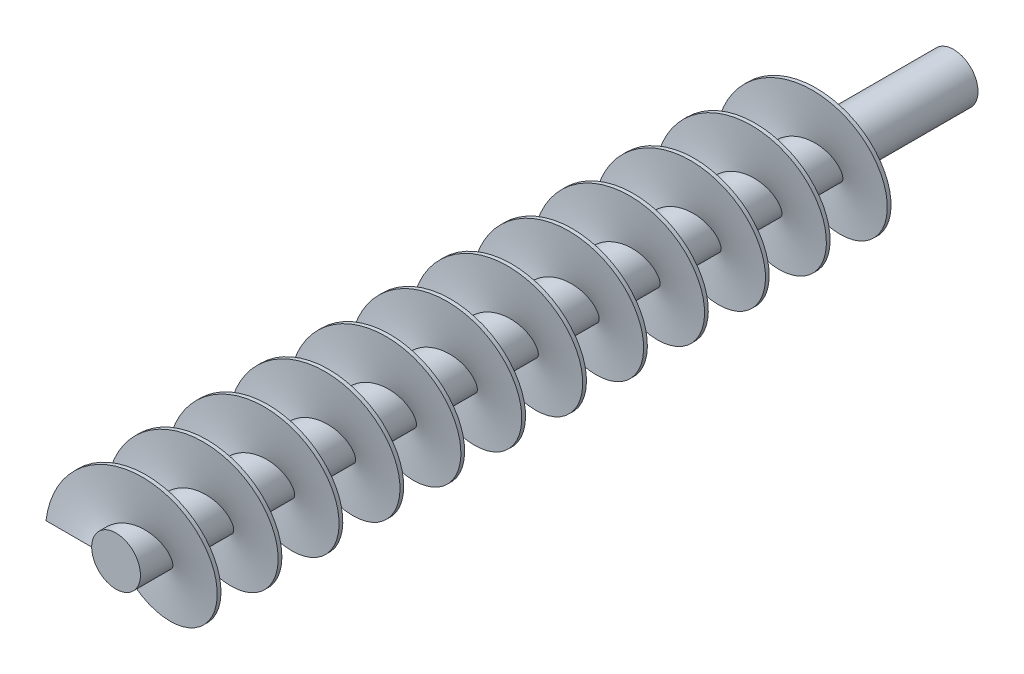
SolidWorks part; units mm, degrees
ref_plane "Front Plane" through (0, 0, 0) normal (0, 0, 1) x (1, 0, 0)
ref_plane "Top Plane" through (0, 0, 0) normal (0, 1, 0) x (1, 0, 0)
ref_plane "Right Plane" through (0, 0, 0) normal (1, 0, 0) x (0, 0, -1)
sketch "Sketch1" plane through (0, 0, 0) normal (0, 0, 1) x (1, 0, 0)
  circle A0 centre (0, 0) radius 3.2
  dimension "D1" = 6.4
extrude "Boss-Extrude2" add sketch "Sketch1" along normal blind 110
sketch "Sketch2" plane through (0, 0, 110) normal (0, 0, 1) x (1, 0, 0)
  circle A0 centre (0, 0) radius 3.2 construction
  circle A1 centre (0, 0) radius 3.2
curve "Helix/Spiral1" pitch 8 height 8 turns 1
ref_plane "Plane1" through (-3.2, 0, 110) normal (0, 0.9292, -0.3697) x (1, 0, 0)
sketch "Sketch3" plane through (-3.2, 0, 110) normal (0, 0.9292, -0.3697) x (1, 0, 0)
  line L1 (0, 0) -> (-6, 0)
  line L2 (0, 0) -> (0, 0.5)
  line L3 (0, 0.5) -> (-6, 0.5)
  line L4 (-6, 0) -> (-6, 0.5)
  dimension "D1" = 6
  dimension "D2" = 0.5
sweep "Sweep1" add profiles "Sketch3" path "Helix/Spiral1"
pattern_linear "LPattern1" count 12 spacing 8 along (0, 0, -1) of bodies 102
